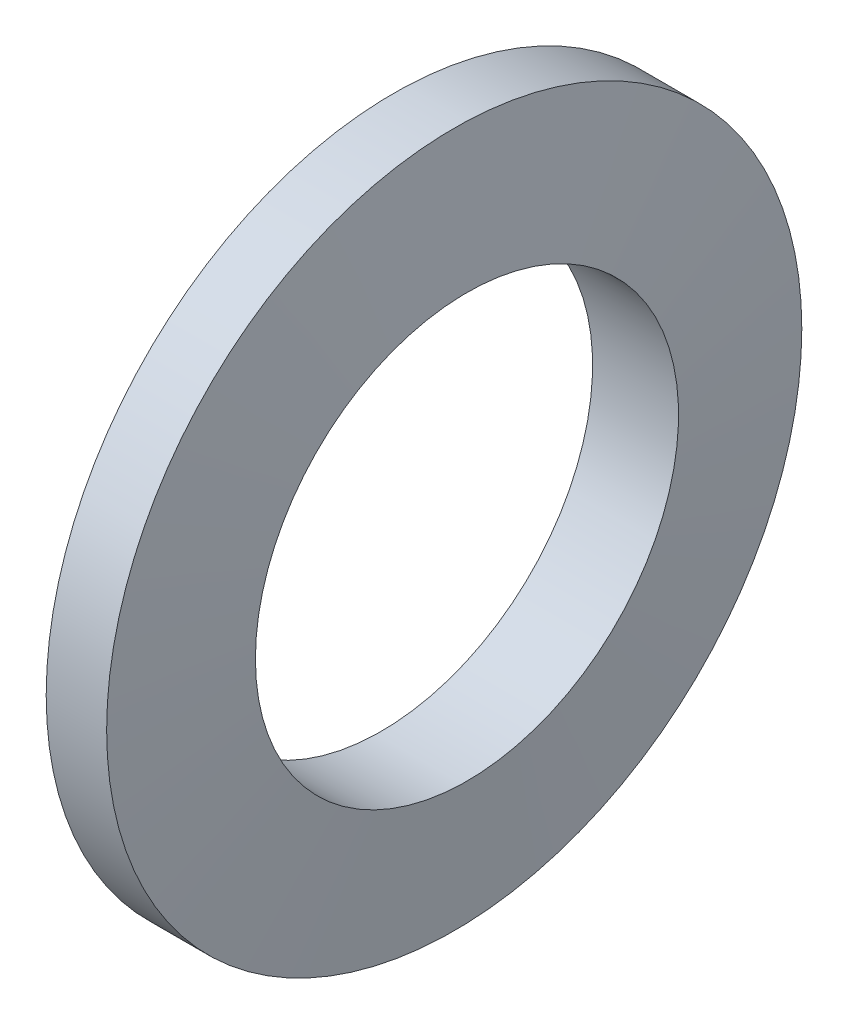
SolidWorks part; units mm, degrees
material "非常高密度 PE (SS)"
ref_plane "前视基准面" through (0, 0, 0) normal (0, 0, 1) x (1, 0, 0)
ref_plane "上视基准面" through (0, 0, 0) normal (0, 1, 0) x (1, 0, 0)
ref_plane "右视基准面" through (0, 0, 0) normal (1, 0, 0) x (0, 0, -1)
sketch "草图1" plane through (0, 0, 0) normal (0, 0, 1) x (1, 0, 0)
  line L0 (0, 33.4048) -> (0, 0) construction
  line L1 (0, 0) -> (46, 0) construction
  line L2 (-2, 23) -> (2, 23)
  line L3 (2, 23) -> (2.8438, 14)
  line L4 (2.8438, 14) -> (-2.8437, 14)
  line L5 (-2.75, 15) -> (2.75, 15) construction
  line L6 (-2, 23) -> (-2.8437, 14)
  point P11 (0, 14)
  point P12 (0, 23)
  point P13 (0, 15)
  dimension "D1" = 15
  dimension "D2" = 28
  dimension "D3" = 46
  dimension "D4" = 4
  dimension "D5" = 5.5
revolve "旋转1" add sketch "草图1" angle 360 about L1
